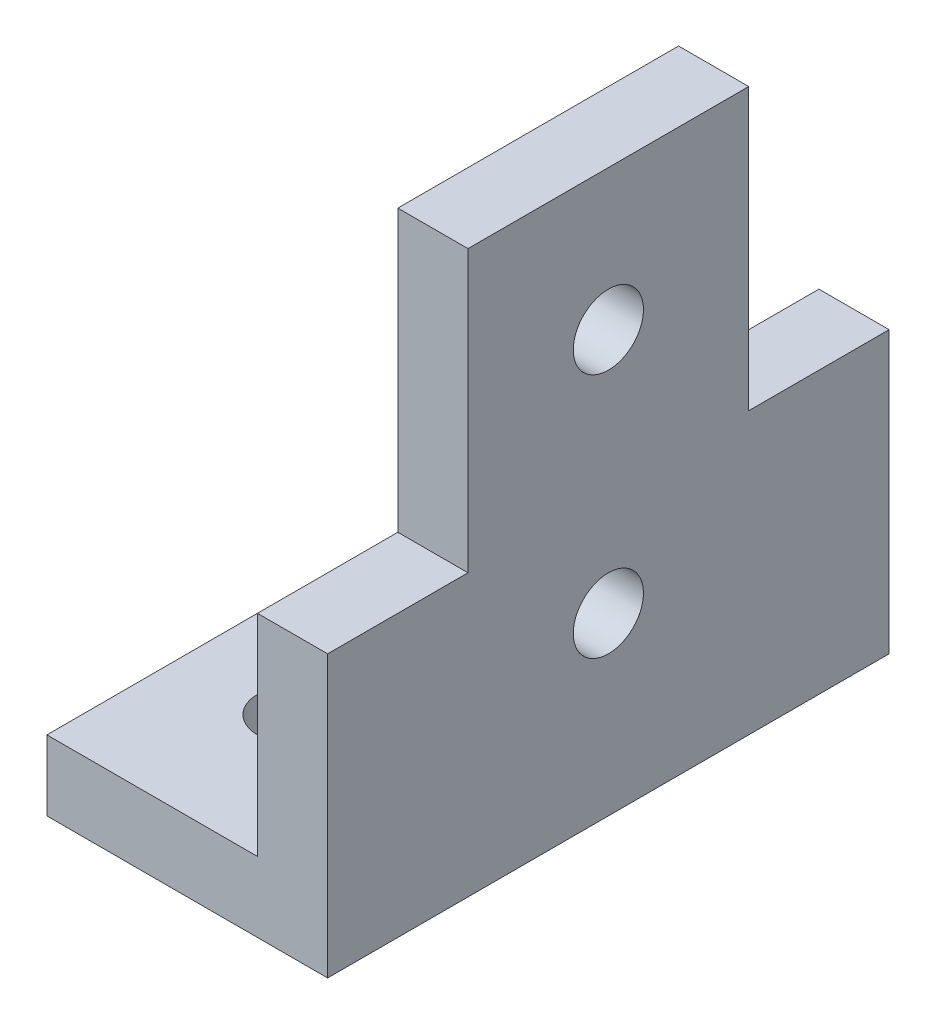
SolidWorks part; units mm, degrees
ref_plane "FRONT" through (0, 0, 0) normal (0, 0, 1) x (1, 0, 0)
ref_plane "TOP" through (0, 0, 0) normal (0, 1, 0) x (1, 0, 0)
ref_plane "RIGHT" through (0, 0, 0) normal (1, 0, 0) x (0, 0, -1)
sketch "Sketch1" plane through (0, 0, 0) normal (0, 0, 1) x (1, 0, 0)
  line L1 (0, 0) -> (25.4, 0)
  line L2 (0, 0) -> (0, 6.35)
  line L3 (0, 6.35) -> (19.05, 6.35)
  line L4 (25.4, 0) -> (25.4, 16.8522)
  line L6 (25.4, 16.8522) -> (25.4, 25.4)
  line L7 (25.4, 25.4) -> (19.05, 25.4)
  line L8 (19.05, 6.35) -> (19.05, 25.4)
  dimension "D1" = 6.35
  dimension "D2" = 6.35
  dimension "D3" = 25.4
  dimension "D4" = 25.4
extrude "Boss-Extrude1" add sketch "Sketch1" along normal blind 50.8
sketch "Sketch2" plane through (0, 6.35, 0) normal (0, 1, 0) x (1, 0, 0)
  line L0 (0, -50.8) -> (0, 0) construction
  line L1 (19.05, 0) -> (0, 0) construction
  line L2 (19.05, -50.8) -> (0, -50.8) construction
  circle A0 centre (9.525, -12.7) radius 3.175
  circle A1 centre (9.525, -38.1) radius 3.175
  dimension "D2" = 6.35
  dimension "D3" = 6.35
  dimension "D1" = 25.4
  dimension "D4" = 9.525
  dimension "D5" = 12.7
  dimension "D6" = 12.7
extrude "Cut-Extrude1" cut sketch "Sketch2" against normal up to next
sketch "Sketch3" plane through (19.05, 0, 0) normal (-1, 0, 0) x (0, 0, 1)
  line L0 (0, 25.4) -> (0, 6.35) construction
  line L1 (50.8, 25.4) -> (0, 25.4) construction
  circle A0 centre (25.4, 15.875) radius 3.175
  dimension "D1" = 6.35
  dimension "D2" = 25.4
  dimension "D3" = 9.525
extrude "Cut-Extrude2" cut sketch "Sketch3" against normal up to next
sketch "Sketch4" plane through (19.05, 0, 0) normal (-1, 0, 0) x (0, 0, 1)
  line L0 (50.8, 25.4) -> (0, 25.4) construction
  line L1 (12.7, 25.4) -> (38.1, 25.4)
  line L2 (12.7, 25.4) -> (12.7, 50.8)
  line L3 (12.7, 50.8) -> (38.1, 50.8)
  line L4 (38.1, 25.4) -> (38.1, 50.8)
  line L5 (0, 25.4) -> (0, 6.35) construction
  circle A0 centre (25.4, 38.1) radius 3.175
  dimension "D4" = 6.35
  dimension "D1" = 25.4
  dimension "D2" = 12.7
  dimension "D3" = 25.4
  dimension "D5" = 12.7
  dimension "D6" = 12.7
extrude "Boss-Extrude2" add sketch "Sketch4" against normal blind 6.35
